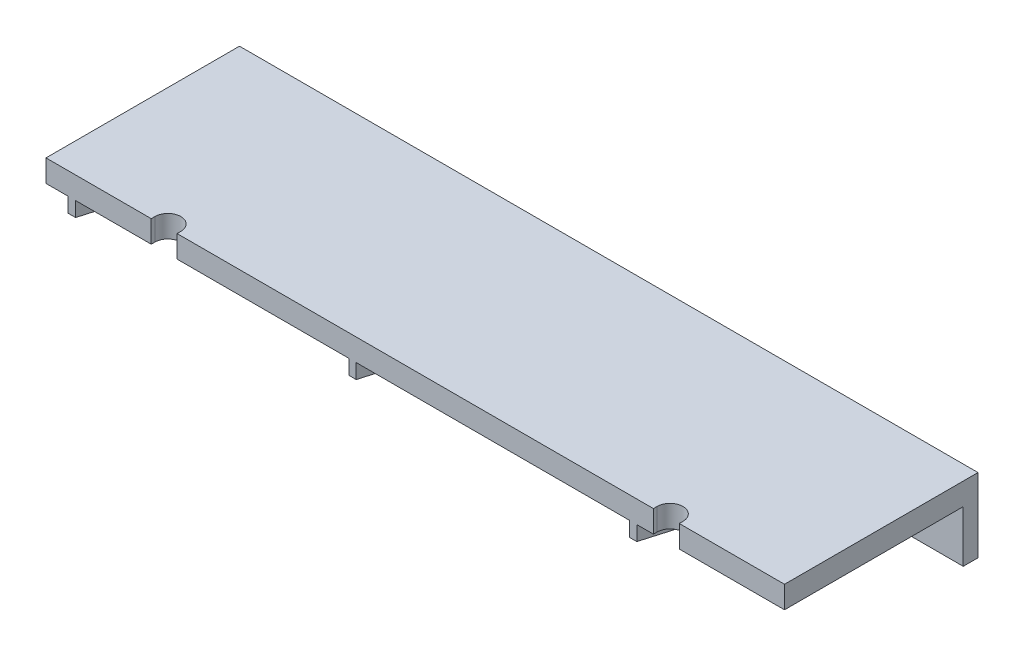
SolidWorks part; units mm, degrees
ref_plane "前视基准面" through (0, 0, 0) normal (0, 0, 1) x (1, 0, 0)
ref_plane "上视基准面" through (0, 0, 0) normal (0, 1, 0) x (1, 0, 0)
ref_plane "右视基准面" through (0, 0, 0) normal (1, 0, 0) x (0, 0, -1)
sketch "草图1" plane through (0, 0, 0) normal (0, 0, 1) x (1, 0, 0)
  line L1 (-500, -50) -> (500, -50)
  line L2 (-500, -50) -> (-500, 50)
  line L3 (-500, 50) -> (500, 50)
  line L4 (500, -50) -> (500, 50)
  line L5 (-500, -50) -> (500, 50) construction
  line L6 (-500, 50) -> (500, -50) construction
  point P0 (0, 0)
  dimension "D1" = 1000
  dimension "D2" = 100
extrude "凸台-拉伸1" add sketch "草图1" along normal blind 20
sketch "草图2" plane through (0, 0, 20) normal (0, 0, 1) x (1, 0, 0)
  line L0 (500, -50) -> (500, 50) construction
  line L1 (-500, 50) -> (500, 50)
  line L2 (-500, 50) -> (-500, 20)
  line L3 (-500, 20) -> (500, 20)
  line L4 (500, 50) -> (500, 20)
  dimension "D1" = 30
extrude "凸台-拉伸2" add sketch "草图2" along normal blind 242 separate body
sketch "草图3" plane through (-500, 0, 0) normal (-1, 0, 0) x (0, 0, 1)
  line L0 (262, 20) -> (20, 20)
  line L1 (20, 20) -> (20, -50)
  line L2 (20, -50) -> (40, -50)
  line L3 (40, -50) -> (262, 0)
  line L4 (262, 0) -> (262, 20)
  dimension "D1" = 20
  dimension "D2" = 20
extrude "凸台-拉伸3" add sketch "草图3" against normal blind 10 from offset 30 offset against normal yes
pattern_linear "阵列(线性)1" count 3 spacing 380 along (1, 0, 0) of "凸台-拉伸3"
sketch "草图4" plane through (0, 50, 0) normal (0, 1, 0) x (1, 0, 0)
  line L0 (-500, -262) -> (-500, 0) construction
  line L1 (500, -262) -> (-500, -262)
  line L2 (500, -262) -> (500, -162)
  line L3 (500, -162) -> (-500, -162)
  line L4 (-500, -262) -> (-500, -162)
  dimension "D1" = 100
extrude "凸台-拉伸4" [suppressed] add sketch "草图4" along normal blind 20 separate body
sketch "草图5" plane through (0, 50, 0) normal (0, 1, 0) x (1, 0, 0)
  line L0 (340, -257) -> (340, -337.436) construction
  line L1 (357.5, -257) -> (357.5, -337.436)
  line L2 (322.5, -257) -> (322.5, -337.436)
  line L3 (-340, -257) -> (-340, -349.0009) construction
  line L4 (-322.5, -257) -> (-322.5, -349.0009)
  line L5 (-357.5, -257) -> (-357.5, -349.0009)
  arc A0 (357.5, -257) -> (322.5, -257) centre (340, -257) ccw
  arc A1 (322.5, -337.436) -> (357.5, -337.436) centre (340, -337.436) ccw
  arc A2 (-322.5, -257) -> (-357.5, -257) centre (-340, -257) ccw
  arc A3 (-357.5, -349.0009) -> (-322.5, -349.0009) centre (-340, -349.0009) ccw
  point P3 (340, -297.218)
  point P8 (-340, -303.0004)
  dimension "D1" = 35
extrude "切除-拉伸1" cut sketch "草图5" against normal through all
